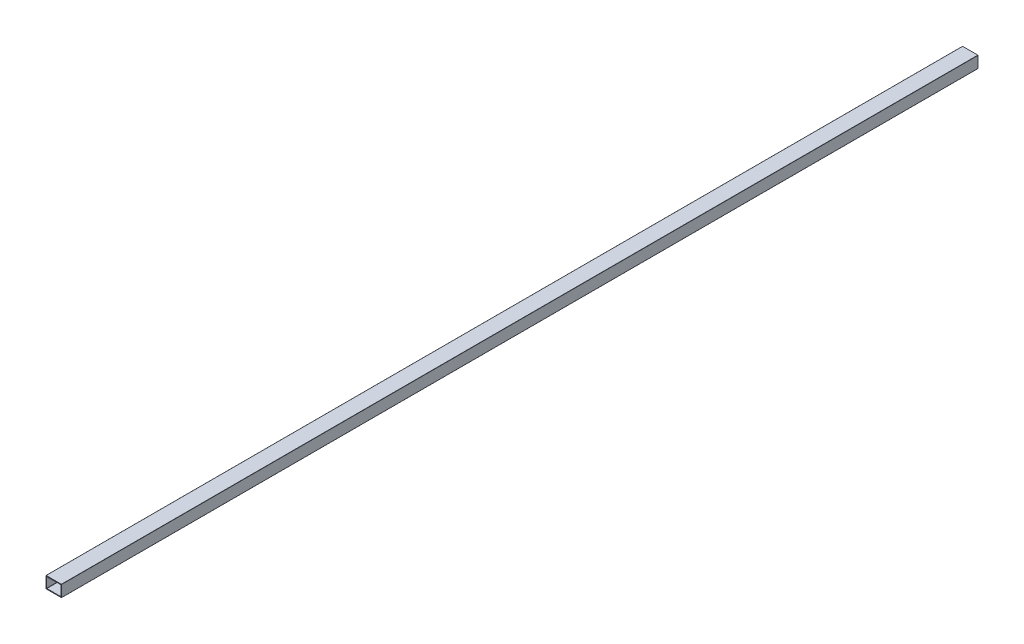
SolidWorks part; units mm, degrees
material "AISI 1035 Acero (SS)"
ref_plane "Alzado" through (0, 0, 0) normal (0, 0, 1) x (1, 0, 0)
ref_plane "Planta" through (0, 0, 0) normal (0, 1, 0) x (1, 0, 0)
ref_plane "Vista lateral" through (0, 0, 0) normal (1, 0, 0) x (0, 0, -1)
sketch "Croquis1" plane through (0, 0, 0) normal (0, 0, 1) x (1, 0, 0)
  line L0 (-46.25, -33.55) -> (-46.25, 33.55)
  line L1 (-50.8, -38.1) -> (50.8, -38.1)
  line L2 (-50.8, -38.1) -> (-50.8, 38.1)
  line L3 (-50.8, 38.1) -> (50.8, 38.1)
  line L4 (50.8, -38.1) -> (50.8, 38.1)
  line L5 (-50.8, -38.1) -> (50.8, 38.1) construction
  line L6 (-50.8, 38.1) -> (50.8, -38.1) construction
  line L7 (-46.25, 33.55) -> (46.25, 33.55)
  line L8 (46.25, -33.55) -> (46.25, 33.55)
  line L9 (-46.25, -33.55) -> (46.25, -33.55)
  point P0 (0, 0)
  dimension "D1" = 76.2
  dimension "D2" = 101.6
  dimension "D3" = 4.55
extrude "Saliente-Extruir1" add sketch "Croquis1" against normal blind 6000
fillet "Redondeo1" radius 1 8 edges at (-46.25, 33.55, -3000) (46.25, 33.55, -3000) (46.25, -33.55, -3000) (-50.8, -38.1, -3000) (-50.8, 38.1, -3000) (-46.25, -33.55, -3000) (50.8, -38.1, -3000) (50.8, 38.1, -3000)
